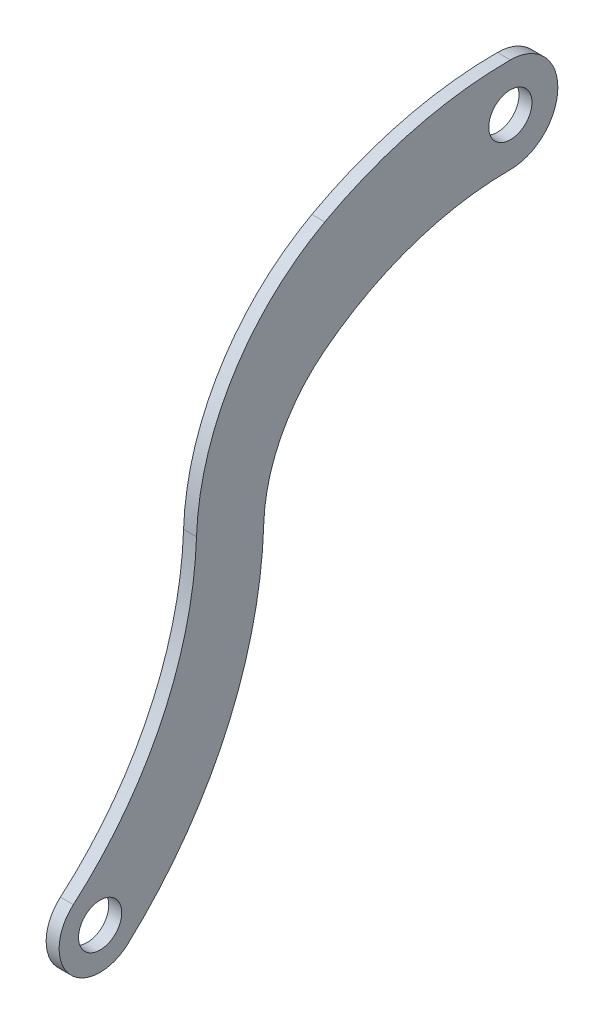
SolidWorks part; units mm, degrees
ref_plane "Front Plane" through (0, 0, 0) normal (0, 0, 1) x (1, 0, 0)
ref_plane "Top Plane" through (0, 0, 0) normal (0, 1, 0) x (1, 0, 0)
ref_plane "Right Plane" through (0, 0, 0) normal (1, 0, 0) x (0, 0, -1)
sketch "Sketch1" plane through (0, 0, 0) normal (1, 0, 0) x (0, 0, -1)
  arc A1 (0, 79) -> (0, 101) centre (0, 90) ccw
  circle A2 centre (0, 0) radius 62.05 construction
  arc A3 (0, 79) -> (-42.9646, 64.2634) centre (0, 9) ccw
  arc A4 (-57.1063, 36.4727) -> (-88.5912, -32.0127) centre (-153.9662, 39.5222) cw
  arc A5 (0, 101) -> (-42.9646, 90) centre (0, 11.5928) ccw
  arc A6 (-42.9646, 90) -> (-72.6772, 41.7178) centre (-15.4469, 39.7822) ccw
  arc A8 (-42.9646, 64.2634) -> (-57.1063, 36.4727) centre (-20.4617, 35.319) ccw
  arc A9 (-72.6772, 41.7178) -> (-101.1986, -17.8009) centre (-154.839, 44.4967) cw
  arc A10 (-101.1986, -17.8009) -> (-88.5912, -32.0127) centre (-95, -25) ccw
  point P1 (-69.7306, 49.5479)
  point P14 (-35.7436, 69.1863)
  point P15 (-42.9646, 64.2634)
  point P16 (-39.3415, 90)
  point P17 (-73.0227, 36.4727)
  point P18 (-42.9646, 90)
  dimension "D1" = 124.1
  dimension "D2" = 90
  dimension "D3" = 70
  dimension "D4" = 22
  dimension "D5" = 9.5
  dimension "D7" = 95
  dimension "D6" = 25
extrude "Boss-Extrude1" add sketch "Sketch1" along normal mid plane 3
sketch "Sketch2" plane through (1.5, 0, 0) normal (1, 0, 0) x (0, 0, -1)
  circle A0 centre (0, 90) radius 5
  circle A1 centre (-95, -25) radius 5
  dimension "D1" = 10
extrude "Cut-Extrude1" cut sketch "Sketch2" against normal through all
